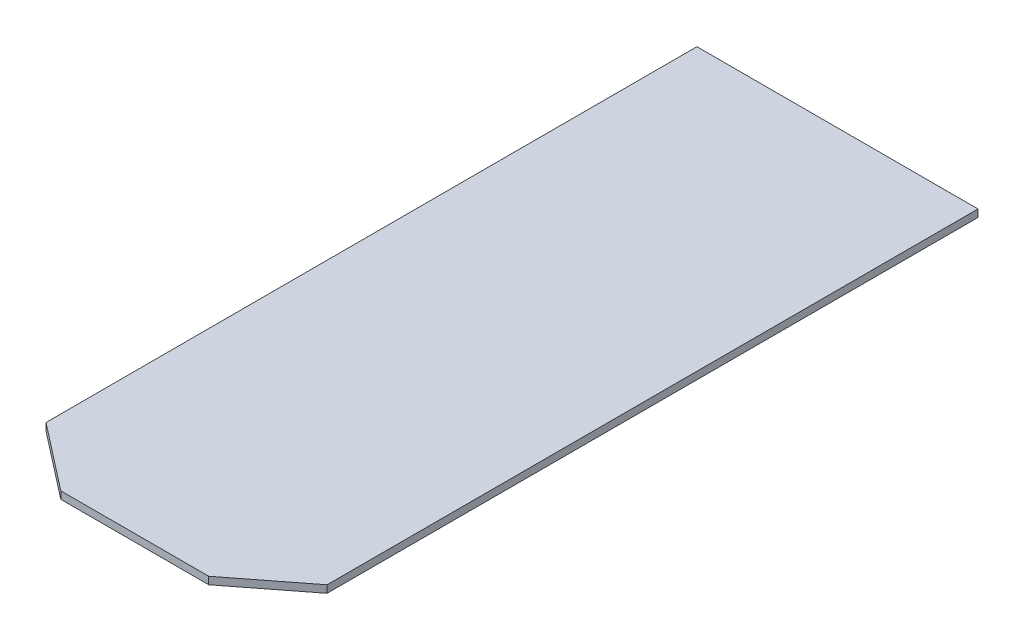
SolidWorks part; units mm, degrees
ref_plane "Front Plane" through (0, 0, 0) normal (0, 0, 1) x (1, 0, 0)
ref_plane "Top Plane" through (0, 0, 0) normal (0, 1, 0) x (1, 0, 0)
ref_plane "Right Plane" through (0, 0, 0) normal (1, 0, 0) x (0, 0, -1)
sketch "Sketch1" plane through (0, 0, 0) normal (0, 1, 0) x (1, 0, 0)
  line L0 (-19, -40.5) -> (-10, -47.5)
  line L1 (19, 47.5) -> (-19, 47.5)
  line L2 (19, 47.5) -> (19, -40.5)
  line L3 (10, -47.5) -> (-10, -47.5)
  line L4 (-19, 47.5) -> (-19, -40.5)
  line L5 (19, 47.5) -> (-19, -47.5) construction
  line L6 (19, -47.5) -> (-19, 47.5) construction
  line L7 (10, -47.5) -> (19, -40.5)
  line L8 (-19, -40.5) -> (-19, -47.5) construction
  line L9 (-19, -47.5) -> (-10, -47.5) construction
  line L10 (10, -47.5) -> (19, -47.5) construction
  line L11 (19, -47.5) -> (19, -40.5) construction
  point P0 (0, 0)
  dimension "D1" = 95
  dimension "D2" = 38
  dimension "D3" = 7
  dimension "D4" = 7
  dimension "D5" = 20
  dimension "D6" = 9
extrude "Boss-Extrude1" add sketch "Sketch1" along normal blind 1
